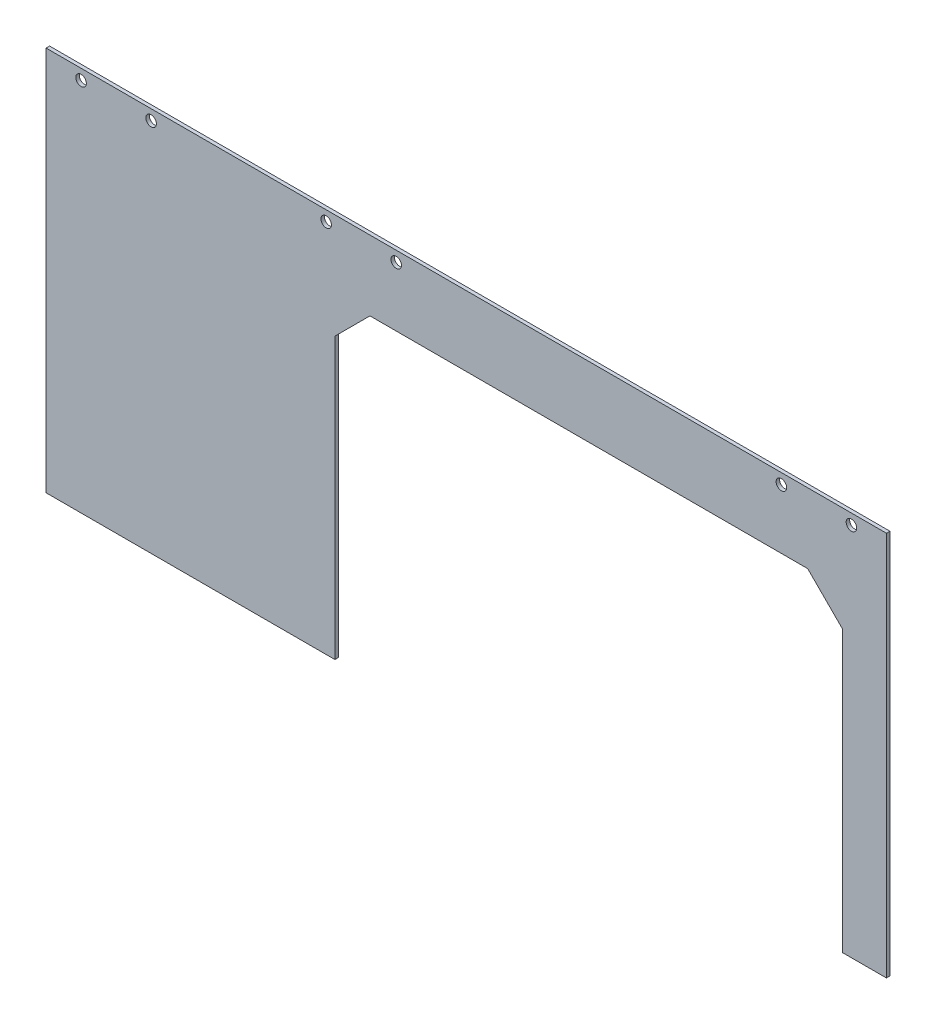
SolidWorks part; units mm, degrees
ref_plane "前视基准面" through (0, 0, 0) normal (0, 0, 1) x (1, 0, 0)
ref_plane "上视基准面" through (0, 0, 0) normal (0, 1, 0) x (1, 0, 0)
ref_plane "右视基准面" through (0, 0, 0) normal (1, 0, 0) x (0, 0, -1)
sketch "草图1" plane through (0, 0, 0) normal (0, 0, 1) x (1, 0, 0)
  line L0 (0, 0) -> (0, 110)
  line L1 (0, 110) -> (240, 110)
  line L4 (82.5, 90) -> (82.5, 0)
  line L5 (82.5, 0) -> (0, 0)
  line L6 (10, 110) -> (10, 107) construction
  line L7 (10, 107) -> (30, 107) construction
  line L8 (120, 110) -> (120, 0) construction
  line L13 (82.5, 90) -> (227.5, 90)
  line L14 (227.5, 90) -> (227.5, 0)
  line L15 (227.5, 0) -> (240, 0)
  line L16 (240, 0) -> (240, 110)
  line L17 (82.5, 0) -> (227.5, 0) construction
  line L18 (155, 90) -> (155, 110) construction
  line L19 (230, 110) -> (230, 107) construction
  line L20 (230, 107) -> (210, 107) construction
  circle A0 centre (10, 107) radius 1.5
  circle A1 centre (30, 107) radius 1.5
  circle A2 centre (210, 107) radius 1.5
  circle A3 centre (230, 107) radius 1.5
  circle A4 centre (80, 107) radius 1.5
  circle A5 centre (100, 107) radius 1.5
  dimension "D5" = 3
  dimension "D10" = 3
  dimension "D1" = 240
  dimension "D2" = 110
  dimension "D3" = 85
  dimension "D4" = 145
  dimension "D6" = 10
  dimension "D7" = 20
  dimension "D8" = 3
  dimension "D9" = 20
  dimension "D11" = 3
  dimension "D12" = 10
  dimension "D13" = 20
extrude "凸台-拉伸1" add sketch "草图1" along normal blind 1
chamfer "倒角1" distance 10 angle 45 2 edges at (227.5, 90, 0.5) (82.5, 90, 0.5)
